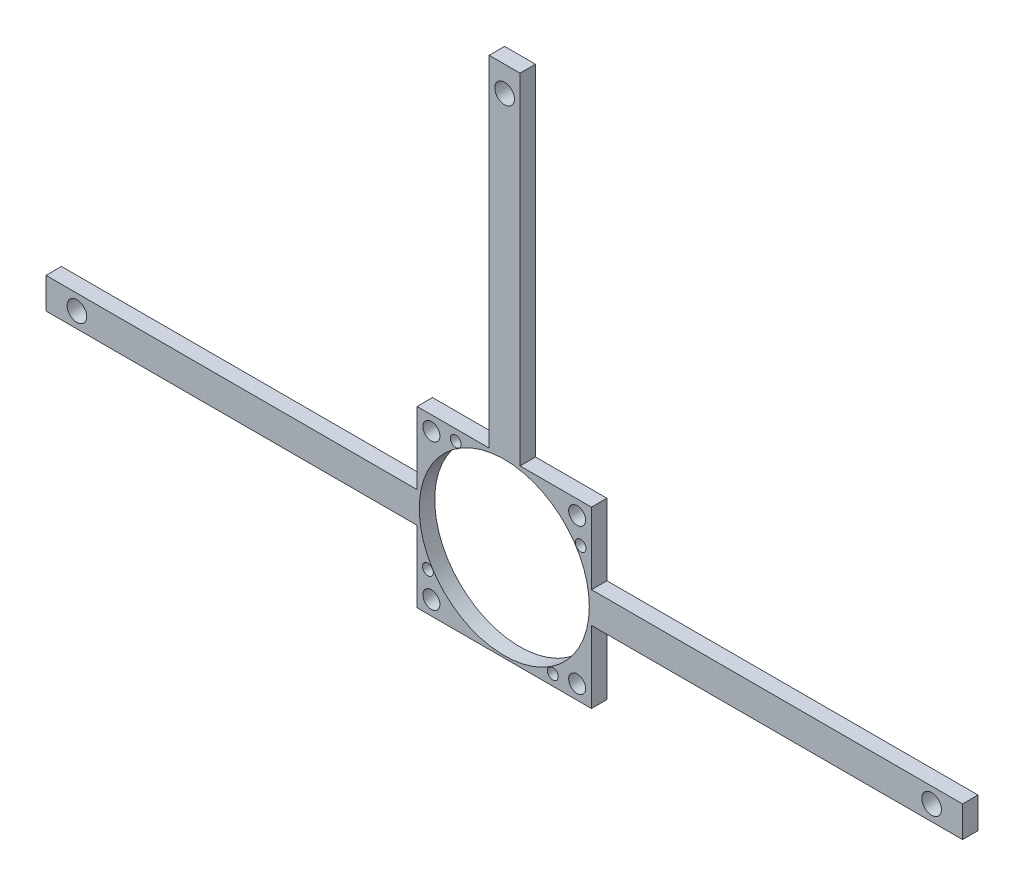
SolidWorks part; units mm, degrees
ref_plane "Alzado" through (0, 0, 0) normal (0, 0, 1) x (1, 0, 0)
ref_plane "Planta" through (0, 0, 0) normal (0, 1, 0) x (1, 0, 0)
ref_plane "Vista lateral" through (0, 0, 0) normal (1, 0, 0) x (0, 0, -1)
sketch "Croquis1" plane through (0, 0, 0) normal (0, 0, 1) x (1, 0, 0)
  line L0 (-28.2, -55.0835) -> (-28.2, -31.8)
  line L1 (-28.2, -88.2) -> (28.2, -88.2)
  line L2 (-28.2, -88.2) -> (-28.2, -65.0835)
  line L3 (-28.2, -31.8) -> (-4.8984, -31.8)
  line L4 (28.2, -88.2) -> (28.2, -64.9165)
  line L5 (-28.2, -88.2) -> (-5.4627, -65.4627) construction
  line L6 (-28.2, -31.8) -> (-5.4627, -54.5373) construction
  line L7 (-148.2, -55.0835) -> (-28.2, -55.0835)
  line L8 (-148.2, -55.0835) -> (-148.2, -65.0835)
  line L9 (-148.2, -65.0835) -> (-28.2, -65.0835)
  line L10 (148.2, -54.9165) -> (148.2, -64.9165)
  line L11 (28.2, -54.9165) -> (28.2, -31.8)
  line L12 (5.1016, 78.2) -> (-4.8984, 78.2)
  line L13 (28.2, -54.9165) -> (148.2, -54.9165)
  line L14 (5.1016, -31.8) -> (28.2, -31.8)
  line L15 (28.2, -64.9165) -> (148.2, -64.9165)
  line L16 (5.1016, -31.8) -> (5.1016, 78.2)
  line L17 (-2.3416, -67.362) -> (28.2, -88.2) construction
  line L18 (-2.3416, -52.638) -> (28.2, -31.8) construction
  line L19 (-4.8984, -31.8) -> (-4.8984, 78.2)
  circle A0 centre (-23.57, -36.43) radius 2.75
  circle A1 centre (23.57, -36.43) radius 2.75
  circle A2 centre (23.57, -83.57) radius 2.75
  circle A3 centre (-23.57, -83.57) radius 2.75
  circle A4 centre (-15.7, -35.3) radius 1.75
  circle A5 centre (24.7, -44.3) radius 1.7478
  circle A6 centre (15.7, -84.7) radius 1.75
  circle A7 centre (-24.7, -75.7) radius 1.75
  circle A8 centre (0, -60) radius 7.7254
  point P0 (0, -60)
  point P23 (-28.2, -60)
  point P29 (0, -31.8)
  dimension "D1" = 120
  dimension "D2" = 120
  dimension "D3" = 10
  dimension "D4" = 10
  dimension "D5" = 110
extrude "Saliente-Extruir1" add sketch "Croquis1" along normal blind 5
sketch "Croquis2" plane through (0, 0, 5) normal (0, 0, 1) x (1, 0, 0)
  line L0 (-148.2, -55.0835) -> (-148.2, -65.0835) construction
  line L1 (148.2, -64.9165) -> (148.2, -54.9165) construction
  line L2 (5.1016, 78.2) -> (-4.8984, 78.2) construction
  circle A0 centre (0.1016, 70) radius 3.175
  circle A1 centre (138.2, -59.9165) radius 3.175
  circle A2 centre (-138.2, -60.0835) radius 3.175
  circle A3 centre (0, -60) radius 7.7254 construction
  circle A4 centre (0, -60) radius 27.5
  point P9 (-148.2, -60.0835)
  point P14 (148.2, -59.9165)
  point P18 (0.1016, 78.2)
  dimension "D1" = 6.35
  dimension "D2" = 6.35
  dimension "D3" = 6.35
  dimension "D4" = 138.2
  dimension "D5" = 138.2
  dimension "D6" = 130
  dimension "D7" = 55
extrude "Cortar-Extruir1" cut sketch "Croquis2" against normal blind 5
